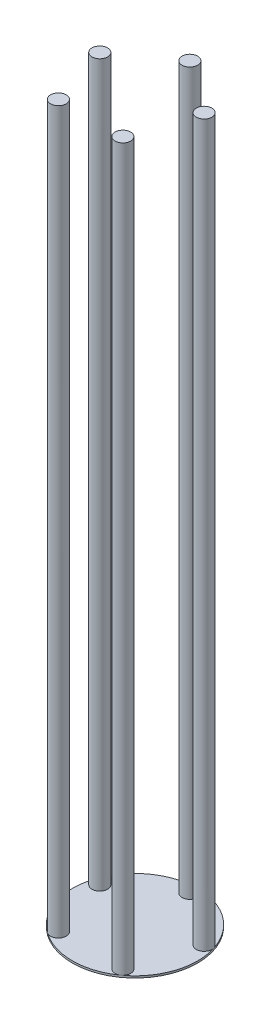
SolidWorks part; units mm, degrees
ref_plane "Front Plane" through (0, 0, 0) normal (0, 0, 1) x (1, 0, 0)
ref_plane "Top Plane" through (0, 0, 0) normal (0, 1, 0) x (1, 0, 0)
ref_plane "Right Plane" through (0, 0, 0) normal (1, 0, 0) x (0, 0, -1)
sketch "Sketch5" plane through (0, 0, 0) normal (0, 1, 0) x (1, 0, 0)
  circle A0 centre (0, 0) radius 101.6
  dimension "D1" = 203.2
extrude "Boss-Extrude9" add sketch "Sketch5" along normal blind 3.175
sketch "Sketch6" plane through (0, 3.175, 0) normal (0, 1, 0) x (1, 0, 0)
  circle A0 centre (0, 88.9) radius 12.7
  circle A1 centre (84.5489, 27.4716) radius 12.7
  circle A2 centre (52.2541, -71.9216) radius 12.7
  circle A3 centre (-52.2541, -71.9216) radius 12.7
  circle A4 centre (-84.5489, 27.4716) radius 12.7
  point P13 (0, 0)
  dimension "D1" = 25.4
  dimension "D2" = 88.9
  dimension "D3" = 5
extrude "Boss-Extrude10" add sketch "Sketch6" along normal blind 1168.4
sketch "Sketch9" plane through (0, 0, 0) normal (0, -1, 0) x (1, 0, 0)
  circle A0 centre (0, -88.9) radius 12.7
  circle A1 centre (-84.5489, -27.4716) radius 12.7
  circle A2 centre (-52.2541, 71.9216) radius 12.7
  circle A3 centre (52.2541, 71.9216) radius 12.7
  circle A4 centre (84.5489, -27.4716) radius 12.7
  point P13 (0, 0)
  dimension "D1" = 88.9
  dimension "D2" = 25.4
  dimension "D3" = 5
sketch "Sketch10" plane through (0, 1171.575, 0) normal (0, 1, 0) x (1, 0, 0)
  circle A0 centre (0, 0) radius 101.6
